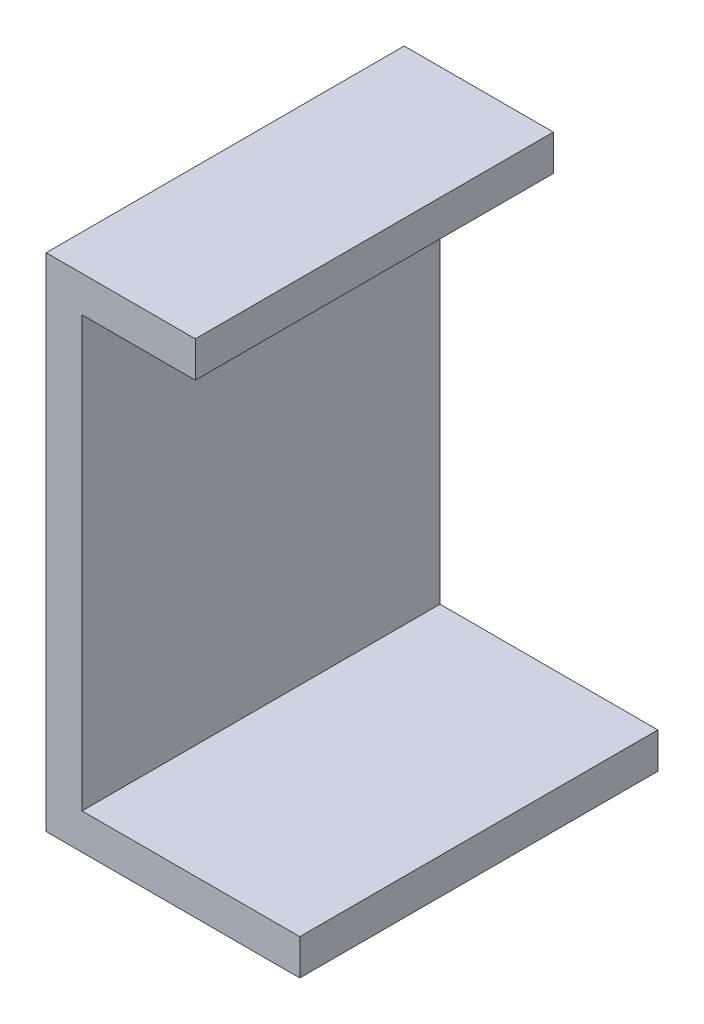
SolidWorks part; units mm, degrees
ref_plane "Front Plane" through (0, 0, 0) normal (0, 0, 1) x (1, 0, 0)
ref_plane "Top Plane" through (0, 0, 0) normal (0, 1, 0) x (1, 0, 0)
ref_plane "Right Plane" through (0, 0, 0) normal (1, 0, 0) x (0, 0, -1)
sketch "Sketch1" plane through (0, 0, 0) normal (0, 0, 1) x (1, 0, 0)
  line L0 (0, 0) -> (0, 42)
  line L1 (0, 42) -> (12.4964, 42)
  line L2 (12.4964, 42) -> (12.4964, 39)
  line L3 (12.4964, 39) -> (3, 39)
  line L4 (3, 39) -> (3, 0)
  line L5 (3, 0) -> (0, 0)
  line L6 (3, 0) -> (21.2508, 0)
  line L7 (21.2508, 0) -> (21.2508, 3)
  line L8 (21.2508, 3) -> (3, 3)
  dimension "D1" = 42
  dimension "D2" = 3
  dimension "D3" = 3
  dimension "D4" = 3
extrude "Boss-Extrude1" add sketch "Sketch1" along normal mid plane 30 contours L5 L4 L3 L2 L1 L0 | L7 L8 L4 L6
